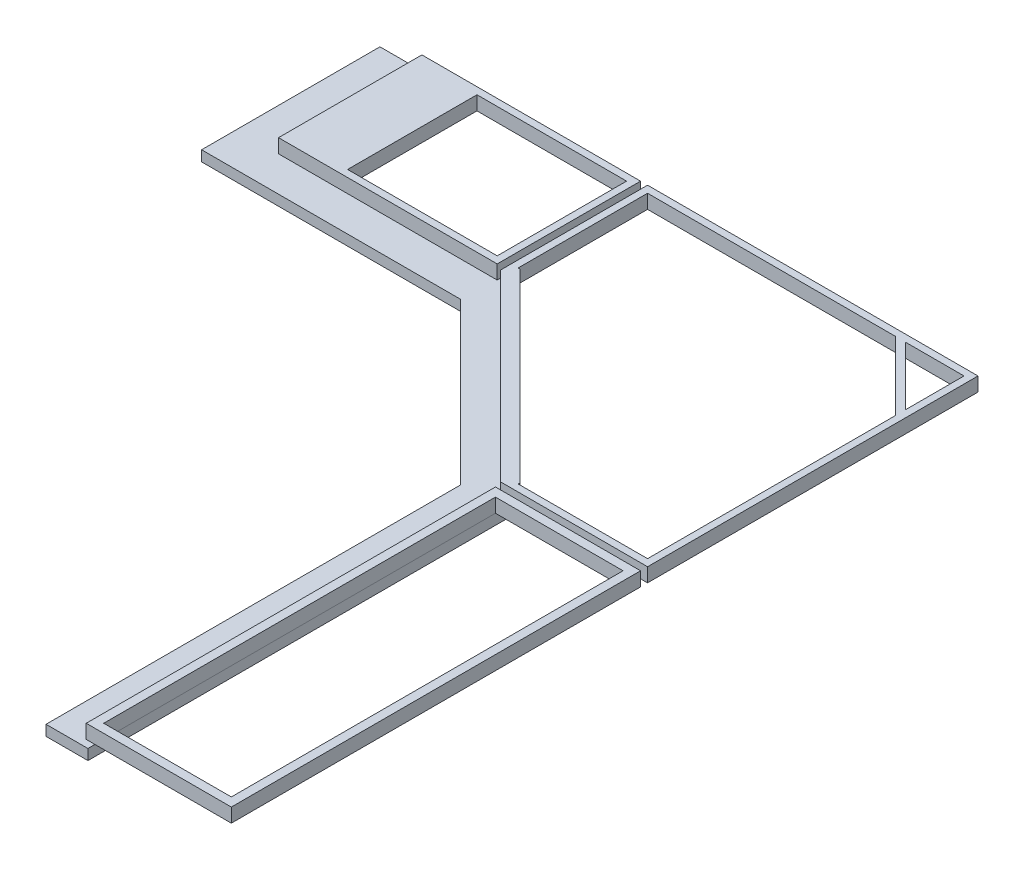
SolidWorks part; units mm, degrees
ref_plane "Front Plane" through (0, 0, 0) normal (0, 0, 1) x (1, 0, 0)
ref_plane "Top Plane" through (0, 0, 0) normal (0, 1, 0) x (1, 0, 0)
ref_plane "Right Plane" through (0, 0, 0) normal (1, 0, 0) x (0, 0, -1)
sketch "Sketch1" plane through (0, 0, 0) normal (0, 1, 0) x (1, 0, 0)
  line L0 (-336.7596, 0) -> (0, -336.7596)
  line L1 (0, -336.7596) -> (-76.2, -368.3227) construction
  line L2 (-76.2, -368.3227) -> (-368.3227, -76.2)
  line L3 (-368.3227, -76.2) -> (-336.7596, 0) construction
  line L4 (-336.7596, 0) -> (-762.2096, 0)
  line L5 (-762.2096, 0) -> (-838.4096, -76.2) construction
  line L6 (-838.4096, -76.2) -> (-368.3227, -76.2)
  line L7 (-838.4096, -76.2) -> (-838.4096, 247.65)
  line L8 (-838.4096, 247.65) -> (-762.2096, 247.65)
  line L9 (-762.2096, 247.65) -> (-762.2096, 0)
  line L10 (0, -336.7596) -> (0, -1120.9846)
  line L11 (0, -1120.9846) -> (-76.2, -1120.9846)
  line L12 (-76.2, -1120.9846) -> (-76.2, -368.3227)
  line L13 (-583.1986, 0) -> (-583.1986, -76.2) construction
  line L14 (-222.2613, -222.2613) -> (-168.3798, -168.3798) construction
  dimension "D1" = 247.65
  dimension "D2" = 425.45
  dimension "D3" = 476.25
  dimension "D4" = 76.2
  dimension "D5" = 784.225
  dimension "D6" = 135
extrude "Moulding" add sketch "Sketch1" along normal blind 19.05 contours L4 L9 L8 L7 L6 L2 L12 L11 L10 L0
sketch "Sketch2" plane through (0, 19.05, 0) normal (0, 1, 0) x (1, 0, 0)
  line L0 (234.95, 234.95) -> (128.7568, 234.95)
  line L1 (-339.725, 234.95) -> (-339.725, -14.112)
  line L2 (-339.725, -14.112) -> (-14.112, -339.725)
  line L3 (-14.112, -339.725) -> (234.95, -339.725)
  line L4 (234.95, -339.725) -> (234.95, 110.7963)
  line L5 (247.65, 247.65) -> (-352.425, 247.65)
  line L6 (-352.425, 247.65) -> (-352.425, -19.3725)
  line L7 (-352.425, -19.3725) -> (-19.3725, -352.425)
  line L8 (-19.3725, -352.425) -> (247.65, -352.425)
  line L9 (247.65, -352.425) -> (247.65, 247.65)
  line L11 (-649.4971, 234.95) -> (-377.825, 234.95)
  line L12 (-649.4971, 234.95) -> (-649.4971, -0.0148)
  line L13 (-649.4971, -0.0148) -> (-377.825, -0.0148)
  line L14 (-377.825, 234.95) -> (-377.825, -0.0148)
  line L17 (-662.1971, 247.65) -> (-762.2096, 247.65)
  line L19 (-662.1971, 247.65) -> (-365.125, 247.65)
  line L20 (-365.125, 247.65) -> (-365.125, -12.7148)
  line L21 (-662.1971, -12.7148) -> (-365.125, -12.7148)
  line L22 (-662.1971, 247.65) -> (-662.1971, -12.7148) construction
  line L23 (0, -336.7596) -> (0, -1120.9846) construction
  line L24 (0, -1092.4096) -> (231.775, -1092.4096)
  line L25 (0, -1092.4096) -> (0, -381)
  line L26 (0, -381) -> (231.775, -381)
  line L27 (231.775, -1092.4096) -> (231.775, -381)
  line L28 (-15.875, -1108.2846) -> (-15.875, -365.125)
  line L29 (-15.875, -365.125) -> (247.65, -365.125)
  line L30 (247.65, -1108.2846) -> (247.65, -365.125)
  line L31 (-15.875, -1108.2846) -> (247.65, -1108.2846)
  line L32 (0, -1120.9846) -> (-76.2, -1120.9846) construction
  line L33 (-838.4096, 247.65) -> (-762.2096, 247.65) construction
  line L34 (-336.7596, 0) -> (0, -336.7596) construction
  line L35 (128.7568, 234.95) -> (234.95, 128.7568)
  line L36 (110.7963, 234.95) -> (234.95, 110.7963)
  line L37 (110.7963, 234.95) -> (-339.725, 234.95)
  line L38 (234.95, 128.7568) -> (234.95, 234.95)
  line L39 (234.95, 234.95) -> (-339.725, 234.95) construction
  line L41 (234.95, -339.725) -> (234.95, 234.95) construction
  line L42 (-662.1971, -12.7148) -> (-762.2096, -12.7148)
  line L43 (-662.1971, -12.7148) -> (-662.1971, 247.65)
  line L44 (-662.1971, 247.65) -> (-762.2096, 247.65)
  line L45 (-762.2096, -12.7148) -> (-762.2096, 247.65)
  dimension "D4" = 12.7
  dimension "D5" = 247.65
  dimension "D6" = 12.7
  dimension "D7" = 574.675
  dimension "D8" = 574.675
  dimension "D9" = 12.7
  dimension "D10" = 12.7
  dimension "D11" = 112.7125
  dimension "D1" = 12.7
  dimension "D2" = 12.7
  dimension "D3" = 15.875
extrude "Boss-Extrude4" add sketch "Sketch2" along normal blind 25.4 separate body
